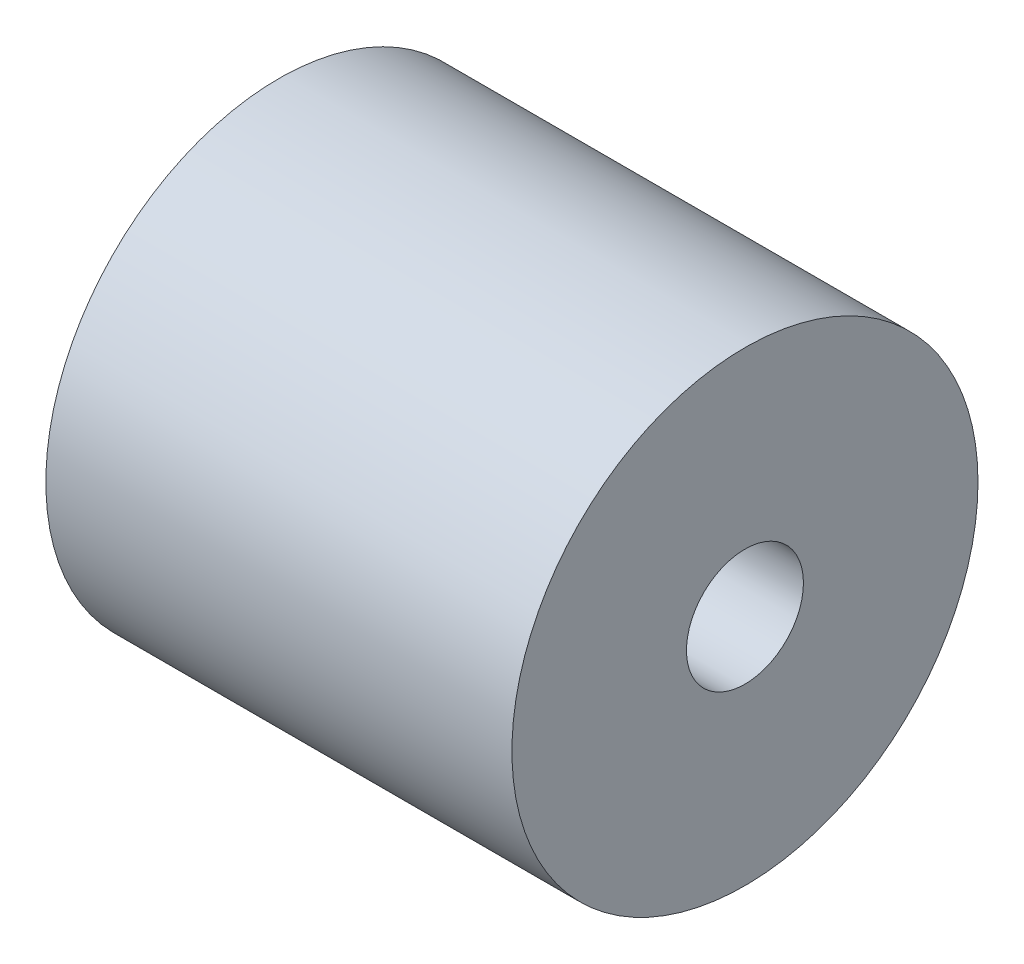
SolidWorks part; units mm, degrees
ref_plane "Alzado" through (0, 0, 0) normal (0, 0, 1) x (1, 0, 0)
ref_plane "Planta" through (0, 0, 0) normal (0, 1, 0) x (1, 0, 0)
ref_plane "Vista lateral" through (0, 0, 0) normal (1, 0, 0) x (0, 0, -1)
sketch "Sketch1" plane through (0, 0, 0) normal (1, 0, 0) x (0, 0, -1)
  circle A0 centre (0, 0) radius 101.6
  circle A1 centre (0, 0) radius 25.5
  dimension "D1" = 203.2
  dimension "D2" = 51
extrude "Boss-Extrude1" add sketch "Sketch1" along normal blind 203.2
